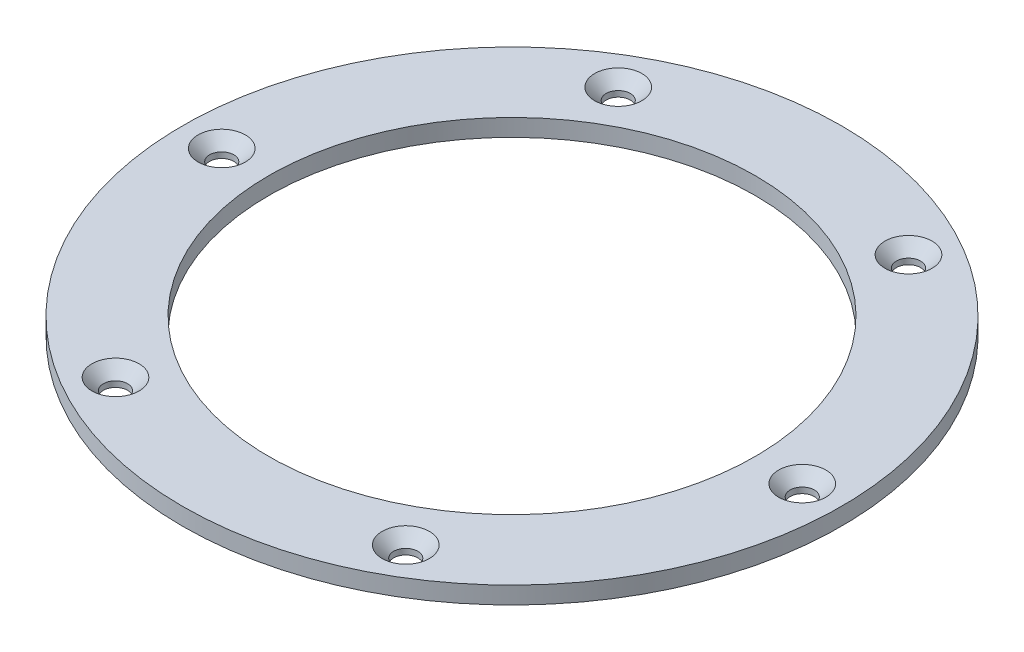
SolidWorks part; units mm, degrees
material "Thornel Mat VMA"
ref_plane "前视基准面" through (0, 0, 0) normal (0, 0, 1) x (1, 0, 0)
ref_plane "上视基准面" through (0, 0, 0) normal (0, 1, 0) x (1, 0, 0)
ref_plane "右视基准面" through (0, 0, 0) normal (1, 0, 0) x (0, 0, -1)
other "Configuration Table"
sketch "草图1" plane through (0, 0, 0) normal (0, 0, 1) x (1, 0, 0)
  line L0 (0, 0) -> (0, 13.1643) construction
  line L1 (57.28, 2.8659) -> (42.28, 2.8659)
  line L2 (57.28, 2.8659) -> (57.28, 5.8659)
  line L3 (57.28, 5.8659) -> (42.28, 5.8659)
  line L4 (42.28, 2.8659) -> (42.28, 5.8659)
  dimension "D1" = 57.28
  dimension "D2" = 15
  dimension "D3" = 3
revolve "旋转1" add sketch "草图1" angle 360 about L0
sketch "草图2" plane through (0, 5.8659, 0) normal (0, 1, 0) x (1, 0, 0)
  circle A0 centre (0, 0) radius 50.45 construction
  circle A2 centre (-50.45, 0) radius 2.1
  circle A3 centre (-25.225, 43.691) radius 2.1
  circle A4 centre (25.225, 43.691) radius 2.1
  circle A5 centre (50.45, 0) radius 2.1
  circle A6 centre (25.225, -43.691) radius 2.1
  circle A7 centre (-25.225, -43.691) radius 2.1
  point P20 (0, 0)
  dimension "D1" = 100.9
  dimension "D2" = 4.2
  dimension "D3" = 6
extrude "切除-拉伸1" cut sketch "草图2" against normal blind 10
chamfer "倒角1" distance 2 angle 45 6 edges at (25.225, 5.8659, -41.591) (-50.45, 5.8659, 2.1) (-25.225, 5.8659, 45.791) (25.225, 5.8659, 45.791) (50.45, 5.8659, 2.1) (-25.225, 5.8659, -41.591)
